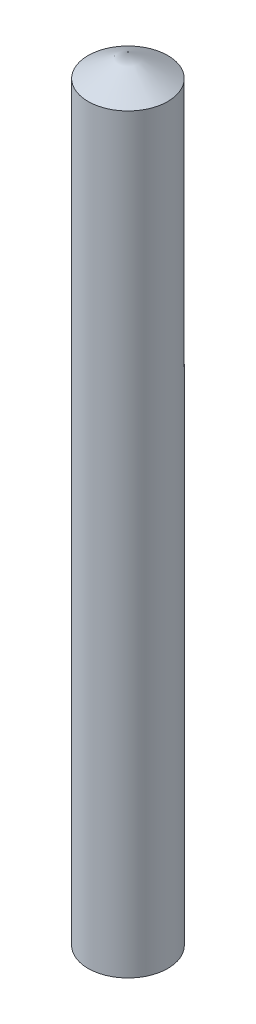
SolidWorks part; units mm, degrees
material "AISI 1020"
ref_plane "Front Plane" through (0, 0, 0) normal (0, 0, 1) x (1, 0, 0)
ref_plane "Top Plane" through (0, 0, 0) normal (0, 1, 0) x (1, 0, 0)
ref_plane "Right Plane" through (0, 0, 0) normal (1, 0, 0) x (0, 0, -1)
sketch "Sketch1" plane through (0, 0, 0) normal (1, 0, 0) x (0, 0, -1)
  line L0 (0, 321.8068) -> (0, -302.6658) construction
  line L1 (-30, 282.6795) -> (-30, -282.6795)
  line L2 (-30, 300) -> (0, 300) construction
  line L3 (-30, -300) -> (0, -300) construction
  line L4 (0, 300) -> (0, -300)
  line L5 (0, 300) -> (-30, 282.6795)
  line L6 (0, 0) -> (-61.5634, 0) construction
  line L7 (0, -300) -> (-30, -282.6795)
  line L8 (-30, 300) -> (-30, 282.6795) construction
  line L9 (-30, -282.6795) -> (-30, -300) construction
  point P5 (-30, 0)
  dimension "D1" = 60
  dimension "D2" = 600
  dimension "D3" = 60
revolve "Revolve1" add sketch "Sketch1" angle 360 about L0
